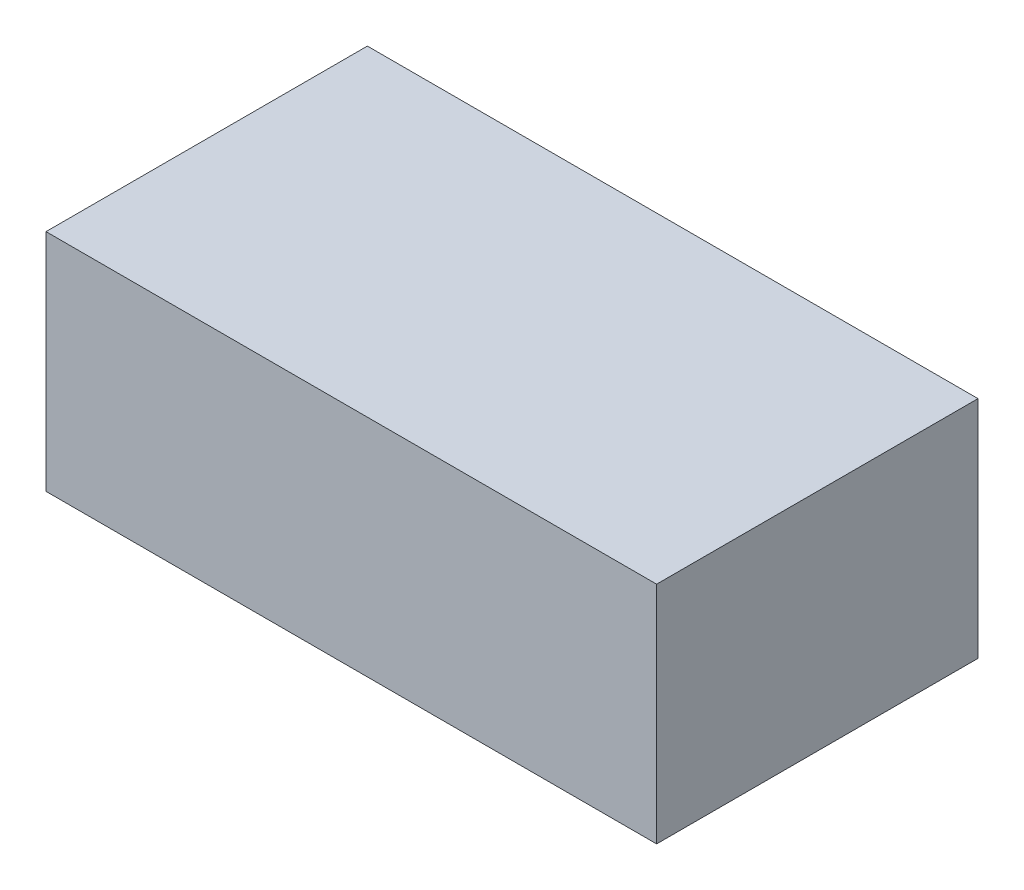
SolidWorks part; units mm, degrees
ref_plane "Front Plane" through (0, 0, 0) normal (0, 0, 1) x (1, 0, 0)
ref_plane "Top Plane" through (0, 0, 0) normal (0, 1, 0) x (1, 0, 0)
ref_plane "Right Plane" through (0, 0, 0) normal (1, 0, 0) x (0, 0, -1)
sketch "Sketch1" plane through (0, 0, 0) normal (0, 1, 0) x (1, 0, 0)
  line L1 (-24.13, -12.7) -> (24.13, -12.7)
  line L2 (-24.13, -12.7) -> (-24.13, 12.7)
  line L3 (-24.13, 12.7) -> (24.13, 12.7)
  line L4 (24.13, -12.7) -> (24.13, 12.7)
  line L5 (-24.13, -12.7) -> (24.13, 12.7) construction
  line L6 (-24.13, 12.7) -> (24.13, -12.7) construction
  point P0 (0, 0)
  dimension "D1" = 48.26
  dimension "D2" = 25.4
extrude "Boss-Extrude1" add sketch "Sketch1" along normal blind 17.78
